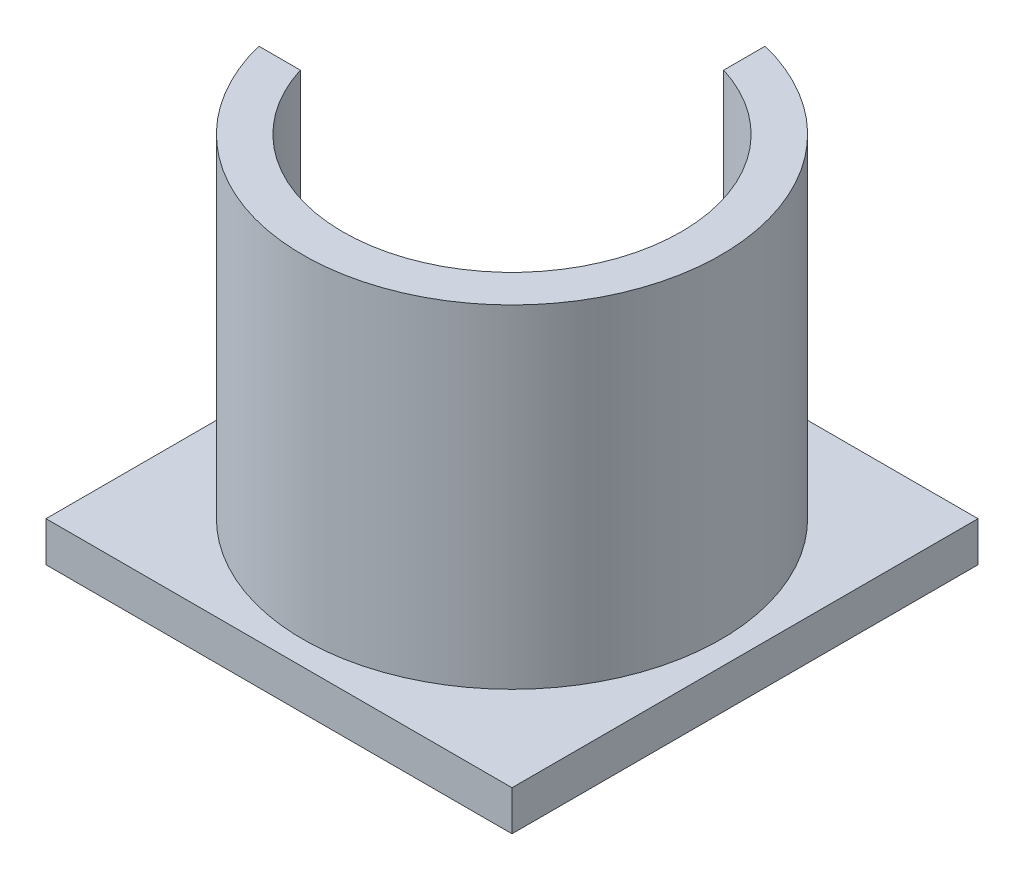
SolidWorks part; units mm, degrees
ref_plane "Front Plane" through (0, 0, 0) normal (0, 0, 1) x (1, 0, 0)
ref_plane "Top Plane" through (0, 0, 0) normal (0, 1, 0) x (1, 0, 0)
ref_plane "Right Plane" through (0, 0, 0) normal (1, 0, 0) x (0, 0, -1)
sketch "Sketch1" plane through (0, 0, 0) normal (0, 1, 0) x (1, 0, 0)
  line L0 (-17.5, -17.5) -> (17.5, -17.5)
  line L1 (-17.5, -17.5) -> (-17.5, 17.5)
  line L2 (17.5, -17.5) -> (17.5, 17.5)
  line L3 (-17.5, 17.5) -> (17.5, 17.5)
  line L4 (-17.5, -17.5) -> (17.5, 17.5) construction
  line L5 (17.5, -17.5) -> (-17.5, 17.5) construction
  point P1 (0, 0)
  dimension "D1" = 35
  dimension "D2" = 35
extrude "Boss-Extrude1" add sketch "Sketch1" along normal blind 3
sketch "Sketch2" plane through (0, 3, 0) normal (0, 1, 0) x (1, 0, 0)
  line L0 (-17.5, -17.5) -> (17.5, 17.5) construction
  line L1 (17.5, -17.5) -> (17.5, 17.5) construction
  line L4 (3.7729, 12.1266) -> (3.7729, 15.2399)
  line L7 (-12.1266, -3.7729) -> (-15.2399, -3.7729)
  arc A0 (-12.1266, -3.7729) -> (3.7729, 12.1266) centre (0, 0) ccw
  arc A1 (-15.2399, -3.7729) -> (3.7729, 15.2399) centre (0, 0) ccw
  circle A3 centre (0, 0) radius 12.7 construction
  circle A4 centre (0, 0) radius 15.7 construction
  point P1 (15.9, 0)
  point P10 (-21.7426, -13.2574)
  point P11 (13.2574, 21.7426)
  point P14 (12.3363, 3.7716)
  dimension "D1" = 25.4
  dimension "D2" = 3
extrude "Boss-Extrude2" add sketch "Sketch2" along normal blind 25 contours A1 L4 A0 L7
sketch "Sketch3" plane through (0, 3, 0) normal (0, 1, 0) x (1, 0, 0)
  line L0 (2.7577, 2.7577) -> (-11.9846, 17.5)
  line L1 (17.5, 17.5) -> (-17.5, 17.5) construction
  line L2 (-2.7577, -2.7577) -> (-17.5, 11.9846)
  line L3 (-17.5, 17.5) -> (-17.5, -17.5) construction
  line L4 (-11.9846, 17.5) -> (-17.5, 17.5)
  line L5 (-17.5, 17.5) -> (-17.5, 11.9846)
  arc A0 (-2.7577, -2.7577) -> (2.7577, 2.7577) centre (0, 0) ccw
  dimension "D1" = 7.8
  dimension "D2" = 0
  dimension "D3" = 45
extrude "Cut-Extrude1" cut sketch "Sketch3" against normal up to next contours L2 L5 L4 L0 A0
